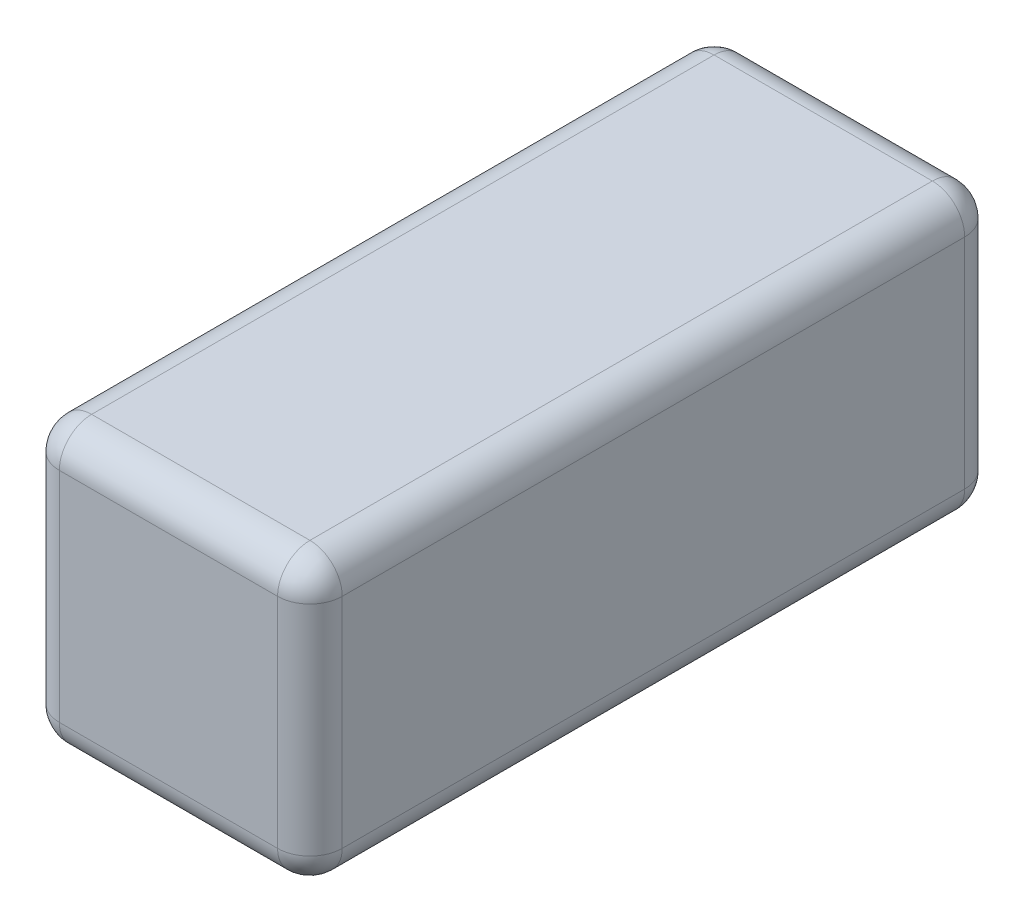
SolidWorks part; units mm, degrees
ref_plane "Front Plane" through (0, 0, 0) normal (0, 0, 1) x (1, 0, 0)
ref_plane "Top Plane" through (0, 0, 0) normal (0, 1, 0) x (1, 0, 0)
ref_plane "Right Plane" through (0, 0, 0) normal (1, 0, 0) x (0, 0, -1)
sketch "Sketch1" plane through (0, 0, 0) normal (0, 0, 1) x (1, 0, 0)
  line L1 (-35, -35) -> (35, -35)
  line L2 (-35, -35) -> (-35, 35)
  line L3 (-35, 35) -> (35, 35)
  line L4 (35, -35) -> (35, 35)
  line L5 (-35, -35) -> (35, 35) construction
  line L6 (-35, 35) -> (35, -35) construction
  point P0 (0, 0)
  dimension "D1" = 70
  dimension "D2" = 70
extrude "Boss-Extrude1" add sketch "Sketch1" along normal blind 170
fillet "Fillet1" radius 8 12 edges at (-35, 0, 170) (35, 0, 170) (-35, -35, 85) (0, -35, 170) (35, -35, 85) (0, -35, 0) (35, 35, 85) (0, 35, 170) (-35, 35, 85) (0, 35, 0) (35, 0, 0) (-35, 0, 0)
